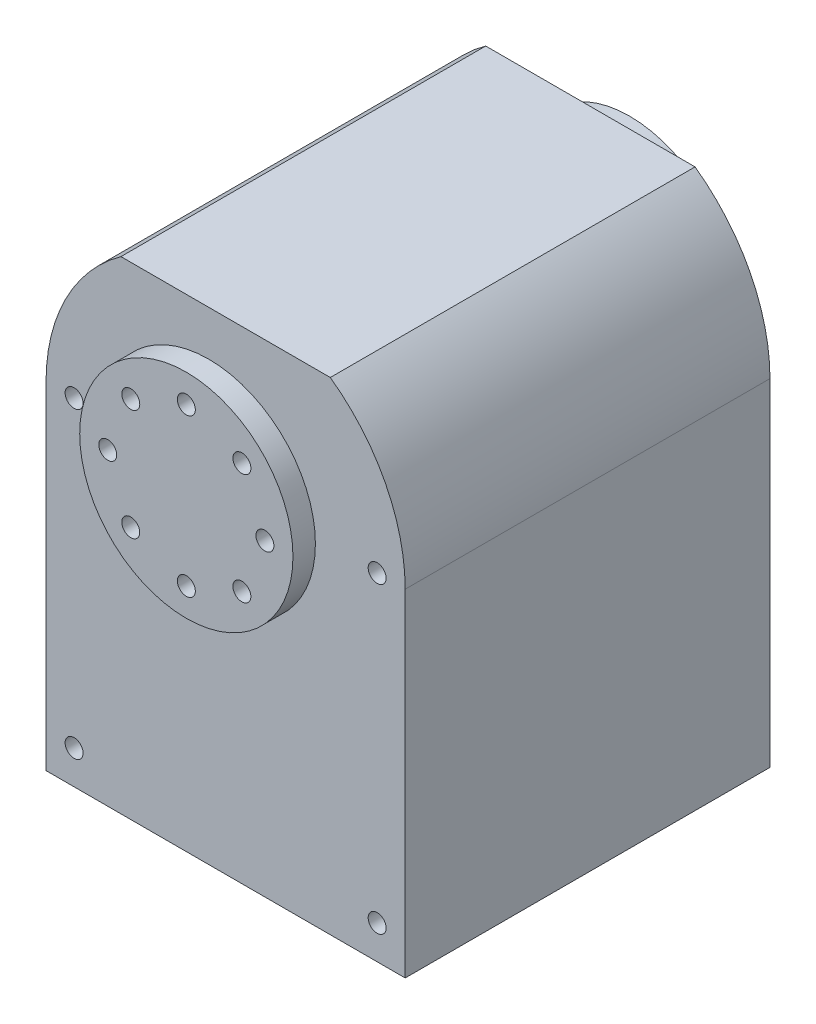
SolidWorks part; units mm, degrees
ref_plane "正面" through (0, 0, 0) normal (0, 0, 1) x (1, 0, 0)
ref_plane "平面" through (0, 0, 0) normal (0, 1, 0) x (1, 0, 0)
ref_plane "右側面" through (0, 0, 0) normal (1, 0, 0) x (0, 0, -1)
sketch "ｽｹｯﾁ1" plane through (0, 0, 0) normal (0, 0, 1) x (1, 0, 0)
  line L0 (-9.3274, 28) -> (9.3274, 28)
  line L1 (16, -15) -> (-16, -15)
  line L2 (16, -15) -> (16, 15)
  line L3 (16, 15) -> (-16, 15) construction
  line L4 (-16, -15) -> (-16, 15)
  line L5 (16, -15) -> (-16, 15) construction
  line L6 (16, 15) -> (-16, -15) construction
  line L7 (0, 28) -> (0, 0) construction
  line L8 (-13.5, -12) -> (13.5, -12) construction
  line L9 (-13.5, 15) -> (13.5, 15) construction
  arc A0 (-16, 15) -> (-9.3274, 28) centre (0, 15) cw
  arc A1 (9.3274, 28) -> (16, 15) centre (0, 15) cw
  circle A2 centre (-13.5, -12) radius 0.8
  circle A3 centre (13.5, -12) radius 0.8
  circle A4 centre (-13.5, 15) radius 0.8
  circle A5 centre (13.5, 15) radius 0.8
  circle A6 centre (0, 16) radius 1.5
  point P0 (0, 0)
  point P16 (0, -12)
  point P19 (0, 15)
  dimension "D4" = 16
  dimension "D6" = 1.6
  dimension "D9" = 3
  dimension "D1" = 30
  dimension "D2" = 32
  dimension "D3" = 43
  dimension "D5" = 27
  dimension "D7" = 3
  dimension "D8" = 27
  dimension "D10" = 1
extrude "ﾎﾞｽ - 押し出し1" add sketch "ｽｹｯﾁ1" along normal blind 32.5
sketch "ｽｹｯﾁ2" plane through (0, 0, 0) normal (0, 0, -1) x (-1, 0, 0)
  circle A0 centre (0, 16) radius 4.5
  dimension "D1" = 9
extrude "ﾎﾞｽ - 押し出し2" add sketch "ｽｹｯﾁ2" along normal blind 1.5
ref_plane "平面1" through (0, 0, 16.25) normal (0, 0, -1) x (-1, 0, 0)
sketch "ｽｹｯﾁ3" plane through (0, 0, -1.5) normal (0, 0, -1) x (-1, 0, 0)
  circle A0 centre (0, 16) radius 9.5
  dimension "D1" = 19
extrude "ﾎﾞｽ - 押し出し3" add sketch "ｽｹｯﾁ3" along normal blind 2
sketch "ｽｹｯﾁ4" plane through (0, 0, -3.5) normal (0, 0, -1) x (-1, 0, 0)
  line L0 (0, 16) -> (0, 25.5) construction
  line L1 (0, 16) -> (6.7175, 22.7175) construction
  line L2 (0, 16) -> (9.5, 16) construction
  line L3 (0, 16) -> (6.7175, 9.2825) construction
  line L4 (0, 16) -> (0, 6.5) construction
  line L5 (0, 16) -> (-6.7175, 9.2825) construction
  line L6 (0, 16) -> (-9.5, 16) construction
  line L7 (0, 16) -> (-6.7175, 22.7175) construction
  circle A0 centre (0, 16) radius 9.5 construction
  circle A1 centre (0, 23) radius 0.8
  circle A2 centre (4.9497, 20.9497) radius 0.8
  circle A3 centre (7, 16) radius 0.8
  circle A4 centre (4.9497, 11.0503) radius 0.8
  circle A5 centre (0, 9) radius 0.8
  circle A6 centre (-4.9497, 11.0503) radius 0.8
  circle A7 centre (-7, 16) radius 0.8
  circle A8 centre (-4.9497, 20.9497) radius 0.8
  point P30 (0, 16)
  dimension "D1" = 1.6
  dimension "D2" = 7
  dimension "D3" = 8
extrude "ｶｯﾄ - 押し出し1" cut sketch "ｽｹｯﾁ4" against normal up to next
mirror "ﾐﾗｰ1" about plane through (0, 0, 16.25) normal (0, 0, -1) of "ﾎﾞｽ - 押し出し2", "ｶｯﾄ - 押し出し1", "ﾎﾞｽ - 押し出し3"
